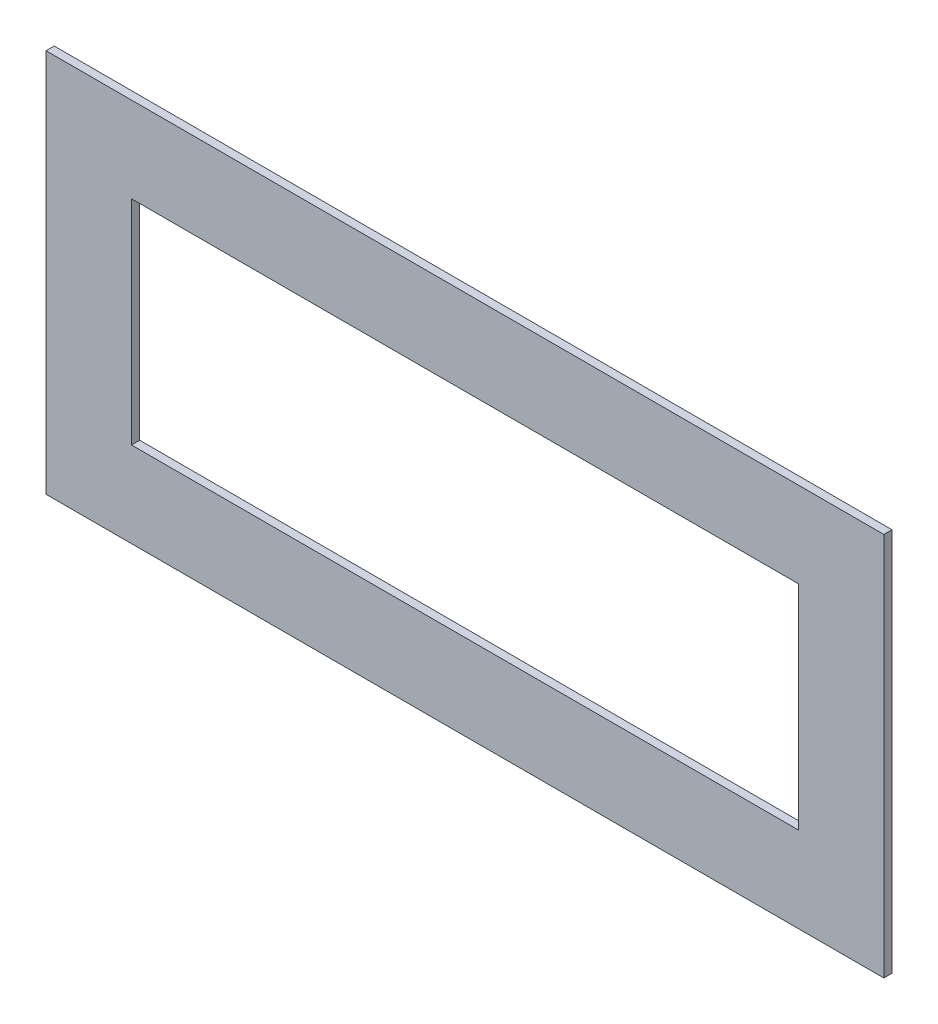
SolidWorks part; units mm, degrees
ref_plane "Front Plane" through (0, 0, 0) normal (0, 0, 1) x (1, 0, 0)
ref_plane "Top Plane" through (0, 0, 0) normal (0, 1, 0) x (1, 0, 0)
ref_plane "Right Plane" through (0, 0, 0) normal (1, 0, 0) x (0, 0, -1)
sketch "Sketch1" plane through (0, 0, 0) normal (0, 0, 1) x (1, 0, 0)
  line L1 (-66.3946, -43.5482) -> (121.3368, -43.5482)
  line L2 (-66.3946, -43.5482) -> (-66.3946, 42.5324)
  line L3 (-66.3946, 42.5324) -> (121.3368, 42.5324)
  line L4 (121.3368, -43.5482) -> (121.3368, 42.5324)
  line L5 (-47.243, -24.3966) -> (102.1852, -24.3966)
  line L6 (-47.243, -24.3966) -> (-47.243, 23.3808)
  line L7 (-47.243, 23.3808) -> (102.1852, 23.3808)
  line L8 (102.1852, -24.3966) -> (102.1852, 23.3808)
  dimension "D1" = 19.1516
  dimension "D2" = 19.1516
  dimension "D3" = 19.1516
  dimension "D4" = 19.1516
  dimension "D5" = 187.7314
  dimension "D6" = 86.0806
  dimension "D7" = 149.4282
  dimension "D8" = 47.7774
extrude "Boss-Extrude1" add sketch "Sketch1" along normal blind 1.8288
